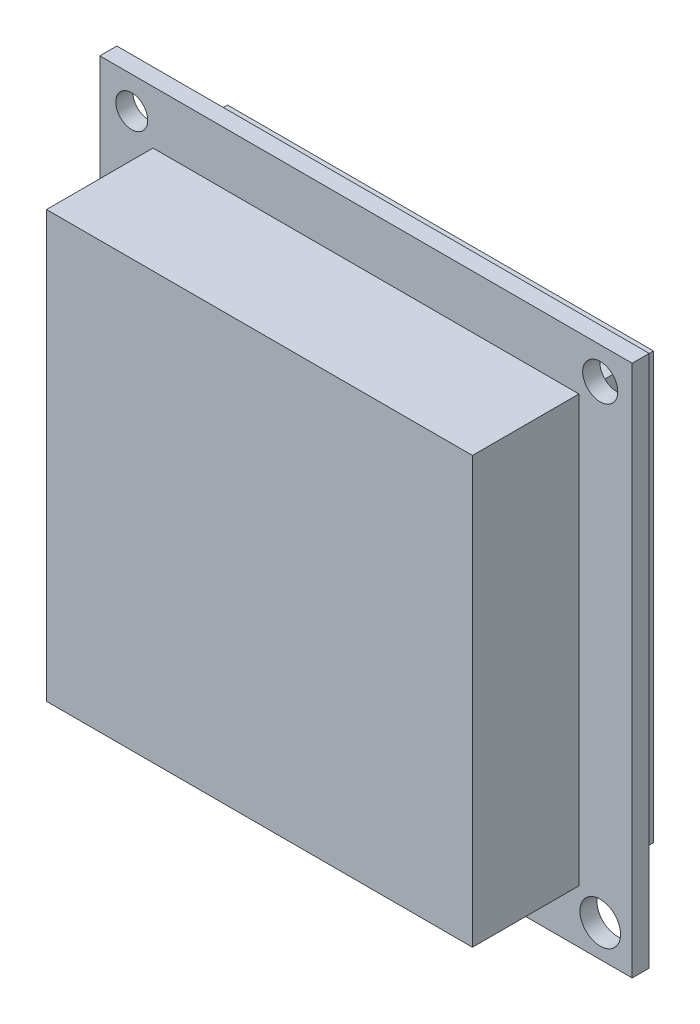
SolidWorks part; units mm, degrees
ref_plane "Front Plane" through (0, 0, 0) normal (0, 0, 1) x (1, 0, 0)
ref_plane "Top Plane" through (0, 0, 0) normal (0, 1, 0) x (1, 0, 0)
ref_plane "Right Plane" through (0, 0, 0) normal (1, 0, 0) x (0, 0, -1)
sketch "Sketch1" plane through (0, 0, 0) normal (0, 0, 1) x (1, 0, 0)
  line L0 (-25, 25) -> (25, 25)
  line L1 (25, 25) -> (25, -25)
  line L2 (25, -25) -> (-25, -25)
  line L3 (-25, -25) -> (-25, 25)
  line L4 (-25, 25) -> (25, -25)
  circle A0 centre (-22, 22) radius 1.5
  circle A1 centre (22, 22) radius 1.6469
  circle A2 centre (22, -22) radius 1.9082
  circle A3 centre (-22, -22) radius 1.7591
  dimension "D3" = 3
  dimension "D1" = 50
  dimension "D2" = 50
  dimension "D4" = 3
  dimension "D5" = 3
  dimension "D6" = 3
  dimension "D7" = 3
extrude "Extrude2" add sketch "Sketch1" along normal mid plane 1.6 contours L0 L4 L1 | L4 L3 L2
sketch "Sketch2" plane through (0, 0, 0.8) normal (0, 0, 1) x (1, 0, 0)
  line L0 (-20, 20) -> (20, 20)
  line L1 (20, 20) -> (20, -20)
  line L2 (20, -20) -> (-20, -20)
  line L3 (-20, -20) -> (-20, 20)
  line L4 (25, 25) -> (25, -25) construction
  line L5 (-25, -25) -> (-25, 25) construction
  line L6 (-25, 25) -> (25, 25) construction
  line L7 (25, -25) -> (-25, -25) construction
  line L8 (-20, 20) -> (20, -20)
  dimension "D1" = 40
  dimension "D2" = 40
extrude "Extrude3" add sketch "Sketch2" along normal blind 10 and the other way blind 7 contours L8 L3 L2 | L0 L8 L1
